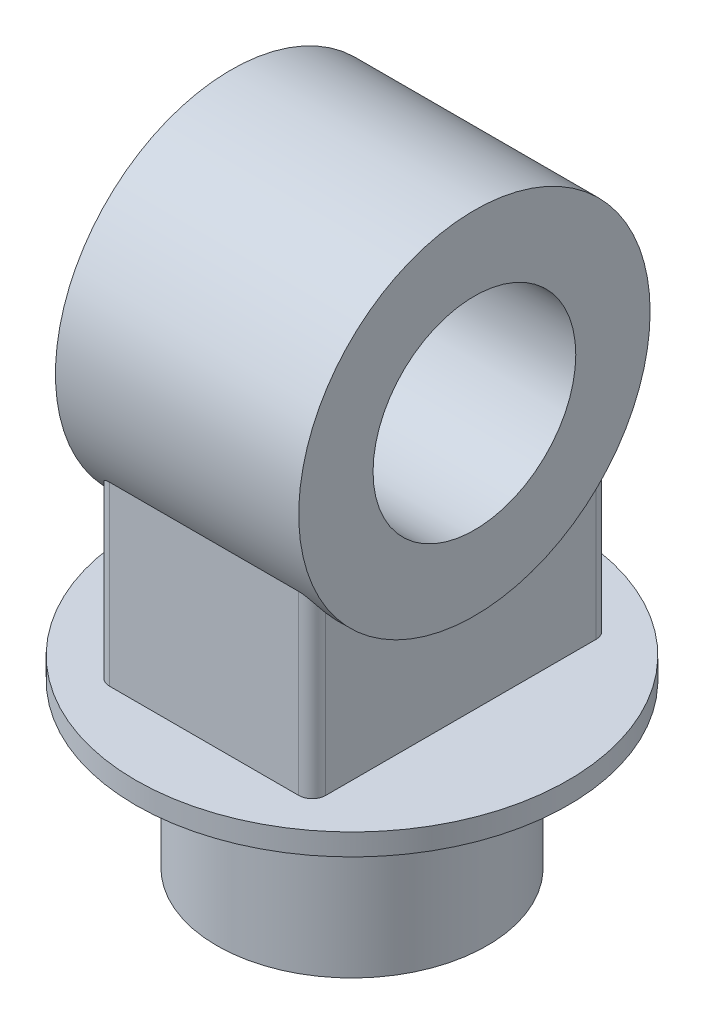
SolidWorks part; units mm, degrees
ref_plane "Front Plane" through (0, 0, 0) normal (0, 0, 1) x (1, 0, 0)
ref_plane "Top Plane" through (0, 0, 0) normal (0, 1, 0) x (1, 0, 0)
ref_plane "Right Plane" through (0, 0, 0) normal (1, 0, 0) x (0, 0, -1)
sketch "Sketch1" plane through (0, 0, 0) normal (0, 1, 0) x (1, 0, 0)
  circle A0 centre (0, 0) radius 100
  dimension "D1" = 200
extrude "Boss-Extrude2" add sketch "Sketch1" against normal blind 120
sketch "Sketch3" plane through (0, 0, 0) normal (0, 1, 0) x (1, 0, 0)
  circle A0 centre (0, 0) radius 160
  dimension "D1" = 320
extrude "Boss-Extrude3" add sketch "Sketch3" along normal blind 16
sketch "Sketch4" plane through (0, 0, 0) normal (1, 0, 0) x (0, 0, -1)
  line L0 (160, 16) -> (-160, 16) construction
  line L1 (-109.4232, 216) -> (110.5768, 216)
  line L2 (-109.4232, 216) -> (-109.4232, 16)
  line L3 (-109.4232, 16) -> (110.5768, 16)
  line L4 (110.5768, 216) -> (110.5768, 16)
  line L5 (-109.4232, 216) -> (110.5768, 16) construction
  line L6 (-109.4232, 16) -> (110.5768, 216) construction
  point P0 (0.5768, 116)
  dimension "D1" = 200
  dimension "D2" = 220
extrude "Boss-Extrude4" add sketch "Sketch4" along normal mid plane 160
sketch "Sketch5" plane through (0, 0, 0) normal (1, 0, 0) x (0, 0, -1)
  line L0 (110.5768, 216) -> (-109.4232, 216) construction
  circle A0 centre (0.5768, 216) radius 130
  dimension "D1" = 260
extrude "Boss-Extrude5" add sketch "Sketch5" along normal mid plane 180
sketch "Sketch6" plane through (0, 0, 0) normal (1, 0, 0) x (0, 0, -1)
  circle A0 centre (0.5768, 216) radius 75
  dimension "D1" = 150
extrude "Cut-Extrude1" cut sketch "Sketch6" against normal mid plane 180 contours A0
fillet "Fillet1" radius 10 4 edges at (-80, 81.359, -110.5768) (-80, 81.359, 109.4232) (80, 81.359, -110.5768) (80, 81.359, 109.4232)
